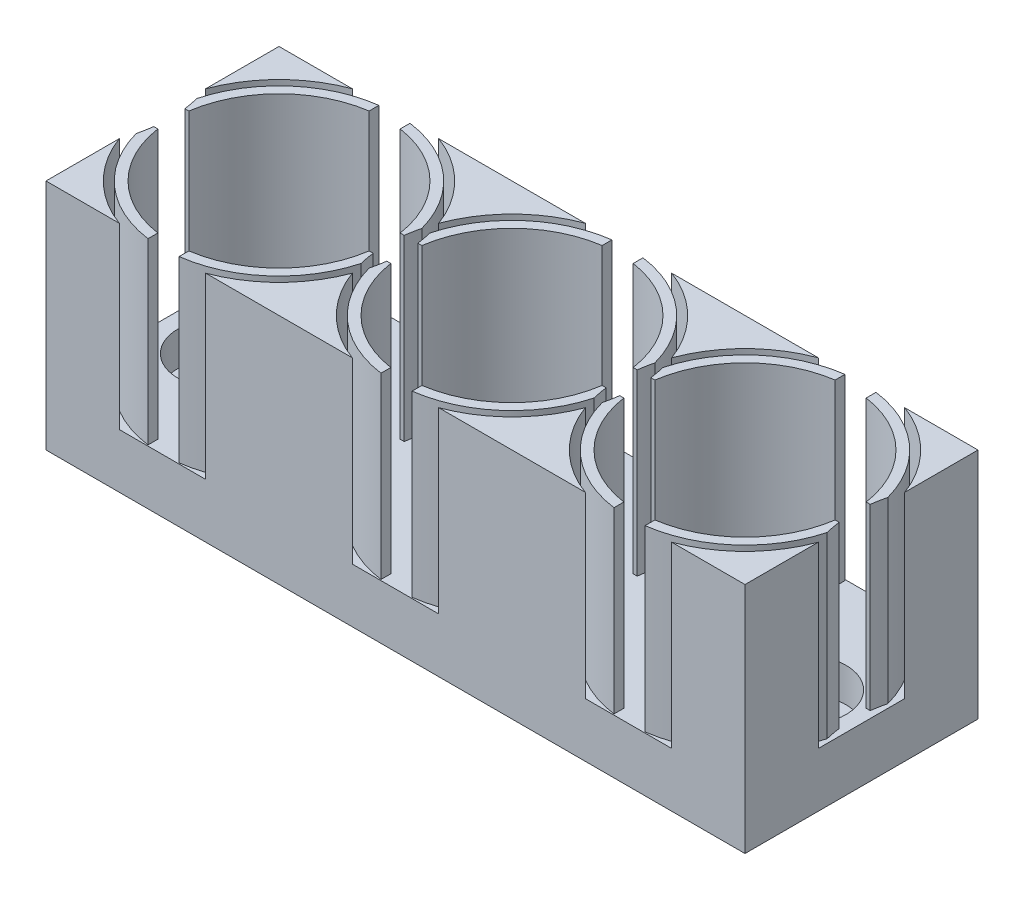
SolidWorks part; units mm, degrees
ref_plane "Front Plane" through (0, 0, 0) normal (0, 0, 1) x (1, 0, 0)
ref_plane "Top Plane" through (0, 0, 0) normal (0, 1, 0) x (1, 0, 0)
ref_plane "Right Plane" through (0, 0, 0) normal (1, 0, 0) x (0, 0, -1)
sketch "Sketch2" plane through (0, 0, 0) normal (0, 1, 0) x (1, 0, 0)
  line L1 (-75, 15) -> (75, 15)
  line L2 (-75, 15) -> (-75, -15)
  line L3 (-75, -15) -> (75, -15)
  line L4 (75, 15) -> (75, -15)
  line L5 (-75, 15) -> (75, -15) construction
  line L6 (-75, -15) -> (75, 15) construction
  point P0 (0, 0)
  dimension "D1" = 150
  dimension "D2" = 30
extrude "Boss-Extrude1" add sketch "Sketch2" along normal blind 30
sketch "Sketch3" plane through (0, 30, 0) normal (0, 1, 0) x (1, 0, 0)
  line L0 (-75, 15) -> (-75, -15) construction
  line L1 (75, 15) -> (-75, 15) construction
  circle A0 centre (-60, 0) radius 13.75
  dimension "D3" = 27.5
  dimension "D1" = 15
  dimension "D2" = 15
extrude "Cut-Extrude1" cut sketch "Sketch3" against normal blind 23
pattern_linear "LPattern1" count 5 spacing 30 along (1, 0, 0) of "Cut-Extrude1"
hole_wizard "CBORE for M4 Hex Socket Head Cap Screw1" positions "Sketch6" profile "Sketch5" counterbore size "M4" standard "DIN" end condition through all
sketch "Sketch6" plane through (0, 7, 0) normal (0, 1, 0) x (-1, 0, 0)
  circle A0 centre (60, 0) radius 13.75 construction
  point P0 (60, 0)
  dimension "D2" = 0
  dimension "D1" = 0
sketch "Sketch5" plane through (-60, 7, 0) normal (1, 0, 0) x (0, 0, 1)
  line L0 (0, 0) -> (0, 7)
  line L1 (0, 7) -> (2.25, 7)
  line L3 (2.25, 7) -> (2.25, 4.4)
  line L4 (2.25, 4.4) -> (4, 4.4)
  line L5 (4, 4.4) -> (4, 0)
  line L7 (4, 0) -> (0, 0)
  line L11 (0, -6.35) -> (0, 107.95) construction
  dimension "Thru Hole Dia." = 4.5
  dimension "Thru Hole Depth" = 7
  dimension "C'Bore Dia." = 8
  dimension "C'Bore Depth" = 4.4
pattern_linear "LPattern2" count 2 spacing 120 along (1, 0, 0) of "CBORE for M4 Hex Socket Head Cap Screw1"
sketch "Sketch7" plane through (0, 30, 0) normal (0, 1, 0) x (1, 0, 0)
  line L1 (-90.5645, -2) -> (90.5645, -2)
  line L2 (-90.5645, -2) -> (-90.5645, 2)
  line L3 (-90.5645, 2) -> (90.5645, 2)
  line L4 (90.5645, -2) -> (90.5645, 2)
  line L5 (-90.5645, -2) -> (90.5645, 2) construction
  line L6 (-90.5645, 2) -> (90.5645, -2) construction
  point P0 (0, 0)
  dimension "D1" = 4
extrude "Cut-Extrude3" cut sketch "Sketch7" against normal blind 23
sketch "Sketch8" plane through (0, 30, 0) normal (0, 1, 0) x (-1, 0, 0)
  line L1 (62, -26.2987) -> (58, -26.2987)
  line L2 (62, -26.2987) -> (62, 23.7013)
  line L3 (62, 23.7013) -> (58, 23.7013)
  line L4 (58, -26.2987) -> (58, 23.7013)
  line L5 (62, -26.2987) -> (58, 23.7013) construction
  line L6 (62, 23.7013) -> (58, -26.2987) construction
  circle A0 centre (60, 0) radius 13.75 construction
  point P0 (60, -1.2987)
  dimension "D1" = 4
  dimension "D2" = 50
  dimension "D3" = 0
extrude "Cut-Extrude4" cut sketch "Sketch8" against normal blind 23
sketch "Skizze1" plane through (0, 7, 0) normal (0, 1, 0) x (-1, 0, 0)
  circle A0 centre (60, 0) radius 15
  circle A1 centre (60, 0) radius 16
extrude "Schnitt-Linear austragen1" cut sketch "Skizze1" along normal through all
pattern_linear "LPattern3" count 5 spacing 30 along (1, 0, 0) of "Cut-Extrude4", "Schnitt-Linear austragen1"
hole_wizard "CBORE for M6 Hex Socket Head Cap Screw1" positions "Sketch10" profile "Sketch9" counterbore size "M6" standard "DIN" end condition through all
sketch "Sketch10" plane through (0, 7, 0) normal (0, 1, 0) x (-1, 0, 0)
  line L0 (75, -15) -> (75, 15) construction
  arc A0 (32, -13.6038) -> (43.6038, -2) centre (30, 0) ccw construction
  point P0 (37.5, 0)
  point P2 (75, 0)
  dimension "D1" = 0
  dimension "D2" = 7.5
sketch "Sketch9" plane through (-37.5, 7, 0) normal (1, 0, 0) x (0, 0, 1)
  line L0 (0, 0) -> (0, 7)
  line L1 (0, 7) -> (3.3, 7)
  line L3 (3.3, 7) -> (3.3, 4.4)
  line L4 (3.3, 4.4) -> (5.5, 4.4)
  line L5 (5.5, 4.4) -> (5.5, 0)
  line L7 (5.5, 0) -> (0, 0)
  line L11 (0, -6.35) -> (0, 107.95) construction
  dimension "Thru Hole Dia." = 6.6
  dimension "Thru Hole Depth" = 7
  dimension "C'Bore Dia." = 11
  dimension "C'Bore Depth" = 4.4
pattern_linear "LPattern4" count 2 spacing 75 along (1, 0, 0) of "CBORE for M6 Hex Socket Head Cap Screw1"
sketch "Skizze2" plane through (-75, 0, 0) normal (-1, 0, 0) x (0, 0, 1)
  line L1 (-15, 0) -> (15, 0)
  line L2 (-15, 0) -> (-15, 30)
  line L3 (-15, 30) -> (15, 30)
  line L4 (15, 0) -> (15, 30)
extrude "Schnitt-Linear austragen2" cut sketch "Skizze2" against normal blind 30
sketch "Skizze3" plane through (75, 0, 0) normal (1, 0, 0) x (0, 0, -1)
  line L1 (15, 0) -> (-15, 0)
  line L2 (15, 0) -> (15, 30)
  line L3 (15, 30) -> (-15, 30)
  line L4 (-15, 0) -> (-15, 30)
extrude "Schnitt-Linear austragen3" cut sketch "Skizze3" against normal blind 30
